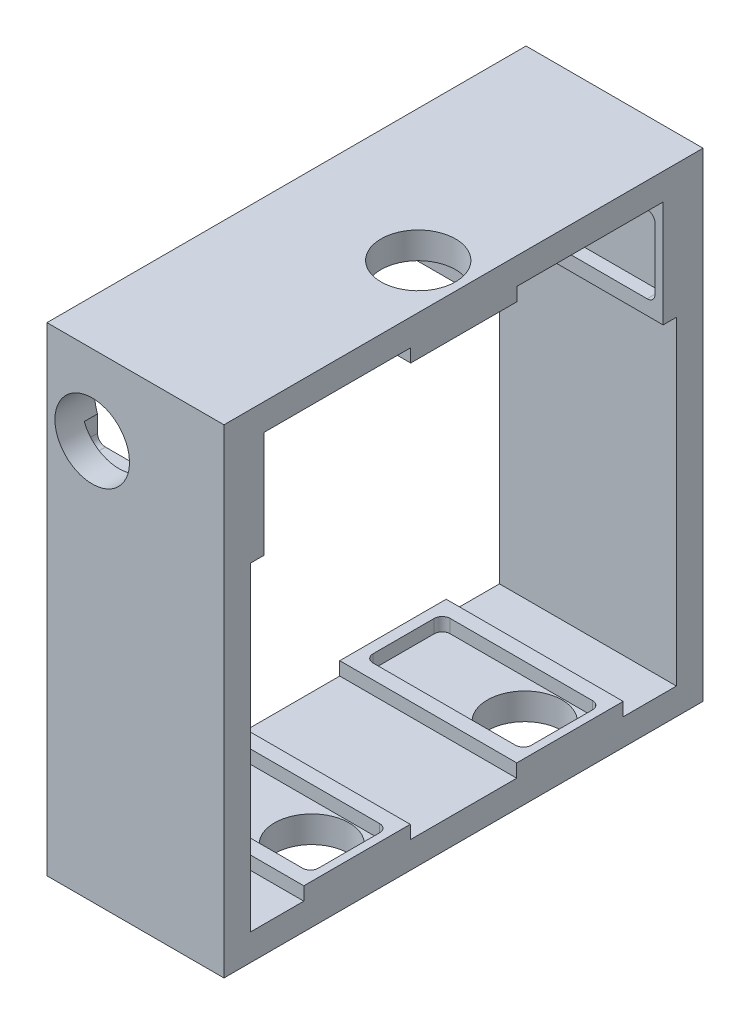
SolidWorks part; units mm, degrees
ref_plane "Front Plane" through (0, 0, 0) normal (0, 0, 1) x (1, 0, 0)
ref_plane "Top Plane" through (0, 0, 0) normal (0, 1, 0) x (1, 0, 0)
ref_plane "Right Plane" through (0, 0, 0) normal (1, 0, 0) x (0, 0, -1)
sketch "Sketch1" plane through (0, 0, 0) normal (0, 0, 1) x (1, 0, 0)
  line L1 (0, 0) -> (66.5, 0)
  line L2 (0, 0) -> (0, 180)
  line L3 (0, 180) -> (66.5, 180)
  line L4 (66.5, 0) -> (66.5, 180)
extrude "Boss-Extrude1" add sketch "Sketch1" along normal blind 180
sketch "Sketch3" plane through (0, 0, 0) normal (-1, 0, 0) x (0, 0, 1)
  line L9 (170, 10) -> (10, 10)
  line L10 (170, 10) -> (170, 170)
  line L11 (170, 170) -> (10, 170)
  line L12 (10, 10) -> (10, 170)
extrude "Cut-Extrude1" cut sketch "Sketch3" against normal blind 180
sketch "Sketch8" plane through (0, 0, 10) normal (0, 0, 1) x (1, 0, 0)
  line L0 (66.5, 170) -> (66.5, 10) construction
  line L1 (0, 170) -> (66.5, 170)
  line L2 (0, 170) -> (0, 130)
  line L3 (0, 130) -> (66.5, 130)
  line L4 (66.5, 170) -> (66.5, 130)
extrude "Boss-Extrude2" add sketch "Sketch8" along normal blind 5
sketch "Sketch10" plane through (0, 0, 170) normal (0, 0, -1) x (-1, 0, 0)
  line L0 (0, 10) -> (0, 170) construction
  line L1 (-66.5, 170) -> (0, 170)
  line L2 (-66.5, 170) -> (-66.5, 130)
  line L3 (-66.5, 130) -> (0, 130)
  line L4 (0, 170) -> (0, 130)
extrude "Boss-Extrude3" add sketch "Sketch10" along normal blind 5
sketch "Sketch5" plane through (0, 180, 0) normal (0, 1, 0) x (1, 0, 0)
  circle A1 centre (49.5, -90) radius 14
extrude "Cut-Extrude3" cut sketch "Sketch5" against normal blind 10
ref_plane "Plane4" through (0, 0, 0) normal (0, 0, -1) x (-1, 0, 0)
sketch "Sketch7" plane through (0, 0, 0) normal (0, -1, 0) x (1, 0, 0)
  circle A2 centre (49.5, 50) radius 14
  circle A3 centre (49.5, 130) radius 14
extrude "Cut-Extrude4" cut sketch "Sketch7" against normal blind 10
sketch "Sketch9" plane through (0, 0, 15) normal (0, 0, 1) x (1, 0, 0)
  line L5 (60.5, 164.5) -> (7.5, 164.5)
  line L12 (63.5, 161.5) -> (63.5, 138.5)
  line L13 (60.5, 135.5) -> (7.5, 135.5)
  line L14 (4.5, 161.5) -> (4.5, 138.5)
  arc A0 (7.5, 135.5) -> (4.5, 138.5) centre (7.5, 138.5) cw
  arc A5 (7.5, 164.5) -> (4.5, 161.5) centre (7.5, 161.5) ccw
  arc A6 (63.5, 161.5) -> (60.5, 164.5) centre (60.5, 161.5) ccw
  arc A7 (63.5, 138.5) -> (60.5, 135.5) centre (60.5, 138.5) cw
  point P3 (63.5, 150)
  dimension "D1" = 3
extrude "Cut-Extrude5" cut sketch "Sketch9" against normal blind 5
sketch "Sketch11" plane through (0, 0, 165) normal (0, 0, -1) x (-1, 0, 0)
  line L0 (-60.5, 164.5) -> (-7, 164.5)
  line L1 (-63.5, 161.5) -> (-63.5, 138.5)
  line L2 (-60.5, 135.5) -> (-7, 135.5)
  line L6 (-4, 161.5) -> (-4, 138.5)
  arc A1 (-7, 164.5) -> (-4, 161.5) centre (-7, 161.5) cw
  arc A2 (-7, 135.5) -> (-4, 138.5) centre (-7, 138.5) ccw
  arc A5 (-63.5, 138.5) -> (-60.5, 135.5) centre (-60.5, 138.5) ccw
  arc A6 (-60.5, 164.5) -> (-63.5, 161.5) centre (-60.5, 161.5) ccw
  point P8 (-57.5, 150)
  dimension "D1" = 3
  dimension "D2" = 3
extrude "Cut-Extrude6" cut sketch "Sketch11" against normal blind 5
sketch "Sketch12" plane through (0, 170, 0) normal (0, -1, 0) x (1, 0, 0)
  line L1 (66.5, 165) -> (66.5, 15) construction
  line L2 (66.5, 69.8335) -> (66.5, 109.8335)
  line L8 (66.5, 109.8335) -> (0, 109.8335)
  line L9 (66.5, 109.8335) -> (66.5, 69.8335)
  line L10 (66.5, 69.8335) -> (0, 69.8335)
  line L11 (0, 109.8335) -> (0, 69.8335)
  line L14 (60.5, 75.3335) -> (7, 75.3335)
  line L15 (63.5, 78.3335) -> (63.5, 101.3335)
  line L16 (60.5, 104.3335) -> (7, 104.3335)
  line L17 (4, 78.3335) -> (4, 101.3335)
  arc A0 (7, 104.3335) -> (4, 101.3335) centre (7, 101.3335) ccw
  arc A1 (63.5, 101.3335) -> (60.5, 104.3335) centre (60.5, 101.3335) ccw
  arc A2 (63.5, 78.3335) -> (60.5, 75.3335) centre (60.5, 78.3335) cw
  arc A3 (7, 75.3335) -> (4, 78.3335) centre (7, 78.3335) cw
  point P6 (63.5, 89.8335)
  point P7 (63.5, 89.8335)
  point P8 (57.5, 90)
  point P19 (57.5, 90)
  point P22 (66.5, 89.8335)
  dimension "D1" = 3
extrude "Boss-Extrude8" add sketch "Sketch12" along normal blind 5
sketch "Sketch15" plane through (0, 0, 0) normal (0, 0, -1) x (-1, 0, 0)
  circle A0 centre (-17, 150) radius 14
extrude "Cut-Extrude7" cut sketch "Sketch15" against normal blind 200
sketch "Sketch16" plane through (0, 10, 0) normal (0, 1, 0) x (1, 0, 0)
  line L1 (0, -10) -> (0, -170) construction
  line L2 (66.5, -10) -> (66.5, -170) construction
  line L4 (63.5, -38.5) -> (63.5, -61.5)
  line L5 (66.5, -30) -> (0, -30)
  line L6 (66.5, -70) -> (66.5, -30)
  line L7 (0, -30) -> (0, -70)
  line L8 (0, -70) -> (66.5, -70)
  line L9 (60.5, -35.5) -> (7, -35.5)
  line L10 (4, -38.5) -> (4, -61.5)
  line L11 (7, -64.5) -> (60.5, -64.5)
  line L20 (66.5, -110) -> (0, -110)
  line L21 (0, -110) -> (0, -150)
  line L22 (0, -150) -> (66.5, -150)
  line L23 (66.5, -150) -> (66.5, -110)
  line L26 (63.5, -141.5) -> (63.5, -118.5)
  line L27 (60.5, -115.5) -> (7, -115.5)
  line L28 (4, -118.5) -> (4, -141.5)
  line L29 (7, -144.5) -> (60.5, -144.5)
  arc A0 (4, -141.5) -> (7, -144.5) centre (7, -141.5) ccw
  arc A1 (63.5, -38.5) -> (60.5, -35.5) centre (60.5, -38.5) ccw
  arc A2 (7, -35.5) -> (4, -38.5) centre (7, -38.5) ccw
  arc A3 (63.5, -61.5) -> (60.5, -64.5) centre (60.5, -61.5) cw
  arc A4 (4, -61.5) -> (7, -64.5) centre (7, -61.5) ccw
  arc A9 (7, -115.5) -> (4, -118.5) centre (7, -118.5) ccw
  arc A10 (63.5, -118.5) -> (60.5, -115.5) centre (60.5, -118.5) ccw
  arc A11 (63.5, -141.5) -> (60.5, -144.5) centre (60.5, -141.5) cw
  point P16 (63.5, -50)
  dimension "D1" = 3
  dimension "D2" = 3
  dimension "D3" = 3
  dimension "D7" = 3
extrude "Boss-Extrude9" add sketch "Sketch16" along normal blind 5
